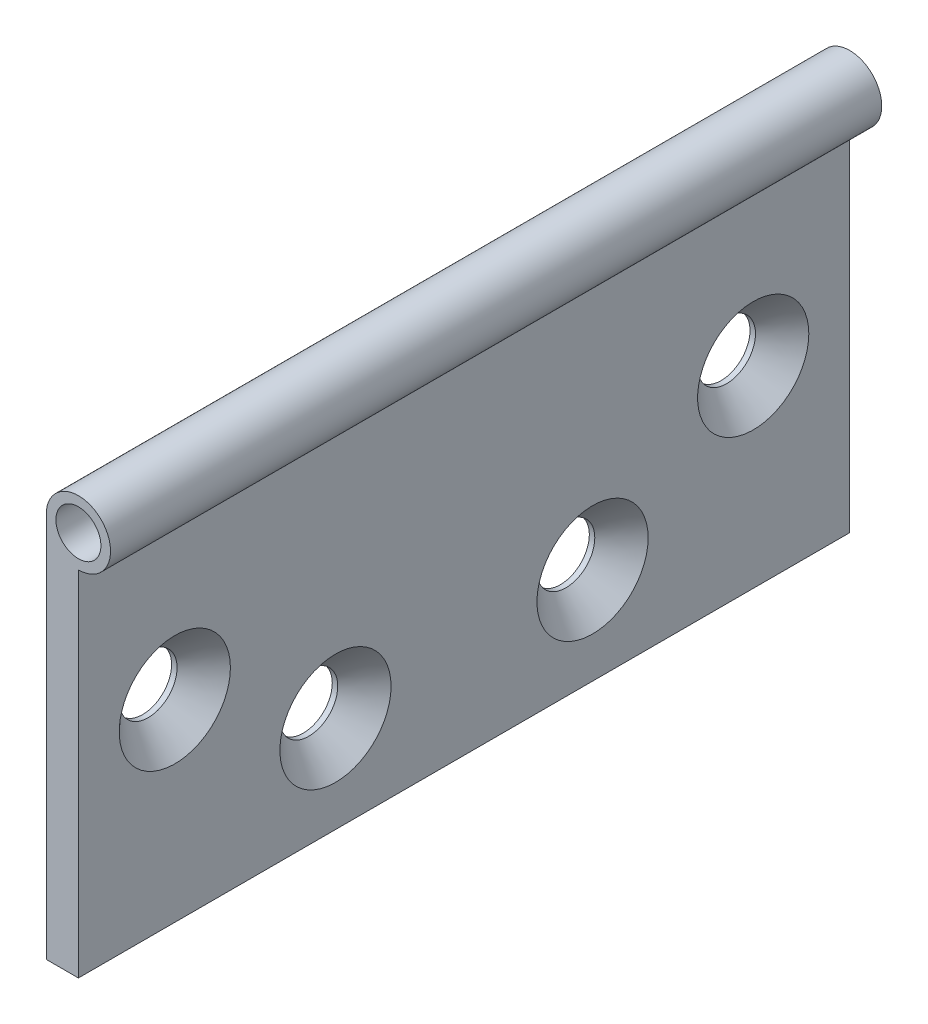
SolidWorks part; units mm, degrees
ref_plane "Front Plane" through (0, 0, 0) normal (0, 0, 1) x (1, 0, 0)
ref_plane "Top Plane" through (0, 0, 0) normal (0, 1, 0) x (1, 0, 0)
ref_plane "Right Plane" through (0, 0, 0) normal (1, 0, 0) x (0, 0, -1)
sketch "Sketch1" plane through (0, 0, 0) normal (0, 0, 1) x (1, 0, 0)
  line L0 (0, 0) -> (0, 60)
  dimension "D1" = 60
extrude "Extrude-Thin1" add sketch "Sketch1" along normal mid plane 120 thin contours L0
sketch "Sketch2" plane through (0, 0, 60) normal (0, 0, 1) x (1, 0, 0)
  circle A0 centre (5, 60) radius 5
sweep "Sweep1" add profiles "Sketch2" path edge at (5, 60, 0)
sketch "Sketch3" plane through (0, 0, 60) normal (0, 0, 1) x (1, 0, 0)
  circle A0 centre (5, 60) radius 3.5
extrude "Cut-Extrude1" cut sketch "Sketch3" against normal through all
hole_wizard "CSK for M8 Flat Head Machine Screw1" positions "Sketch4" profile "Sketch5" countersink size "M8" standard "ANSI Metric" end condition through all
sketch "Sketch4" plane through (5, 0, 0) normal (1, 0, 0) x (0, 0, -1)
  line L0 (-60, 0) -> (60, 0) construction
  line L1 (-60, 0) -> (-60, 55) construction
  point P0 (-45, 30)
  point P2 (-20, 15)
  dimension "D1" = 15
  dimension "D2" = 40
  dimension "D3" = 15
  dimension "D4" = 30
sketch "Sketch5" plane through (5, 30, 45) normal (0, 1, 0) x (0, 0, -1)
  line L0 (0, 0) -> (0, 5)
  line L1 (0, 5) -> (4.5, 5)
  line L2 (4.5, 5) -> (4.5, 4.15)
  line L3 (4.5, 4.15) -> (8.65, 0)
  line L5 (8.65, 0) -> (0, 0)
  line L6 (-4.5, 4.15) -> (-8.65, 0) construction
  line L11 (0, -6.35) -> (0, 107.95) construction
  dimension "Thru Hole Dia." = 9
  dimension "Thru Hole Depth" = 5
  dimension "Near C'Sink Dia." = 17.3
  dimension "Near C'Sink Angle" = 90
mirror "Mirror1" about plane through (0, 0, 0) normal (0, 0, 1) of "CSK for M8 Flat Head Machine Screw1"
equation "\"D4@Sketch4\"= 60mm / 2"
equation "\"D2@Sketch4\"= 120mm / 3"
